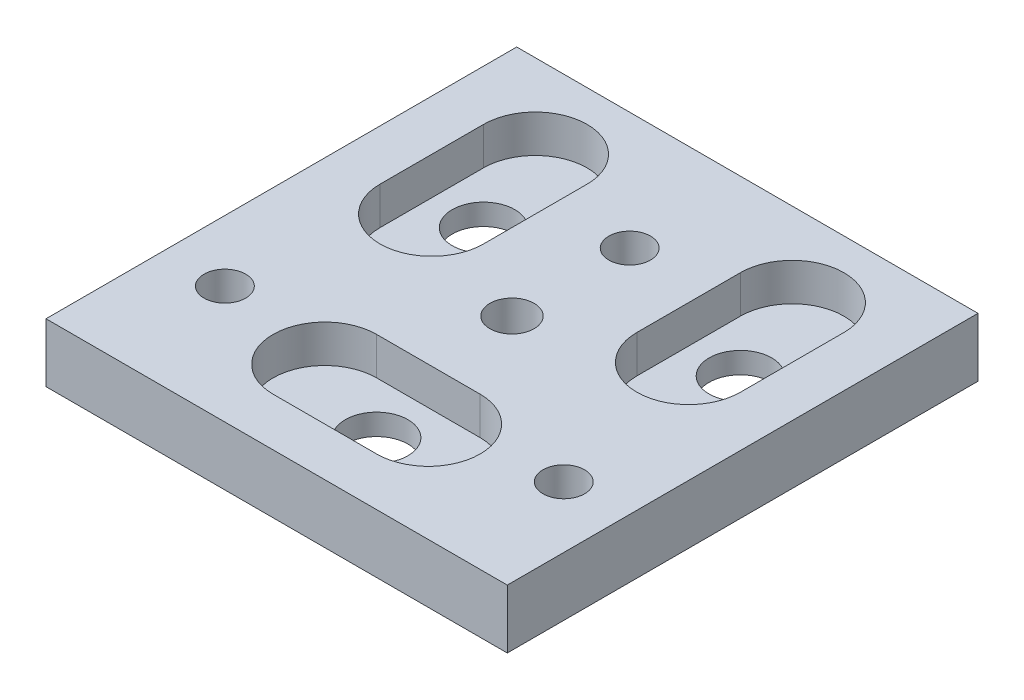
SolidWorks part; units mm, degrees
material "AISI 304"
ref_plane "Front Plane" through (0, 0, 0) normal (0, 0, 1) x (1, 0, 0)
ref_plane "Top Plane" through (0, 0, 0) normal (0, 1, 0) x (1, 0, 0)
ref_plane "Right Plane" through (0, 0, 0) normal (1, 0, 0) x (0, 0, -1)
sketch "Sketch1" plane through (0, 0, 0) normal (0, 1, 0) x (1, 0, 0)
  line L1 (-24.892, 25.4) -> (24.892, 25.4)
  line L2 (-24.892, 25.4) -> (-24.892, -25.4)
  line L3 (-24.892, -25.4) -> (24.892, -25.4)
  line L4 (24.892, 25.4) -> (24.892, -25.4)
  dimension "D1" = 50.8
  dimension "D2" = 49.784
  dimension "D3" = 24.892
  dimension "D4" = 25.4
extrude "Boss-Extrude1" add sketch "Sketch1" along normal blind 6.35
hole_wizard "#8 Clearance Hole1" positions "Sketch5" profile "Sketch4" hole size "#8" standard "ANSI Inch" end condition through all
sketch "Sketch5" plane through (0, 6.35, 0) normal (0, 1, 0) x (1, 0, 0)
  line L1 (24.892, 25.4) -> (-24.892, 25.4) construction
  line L3 (-24.892, -25.4) -> (24.892, -25.4) construction
  point P0 (-18.288, 12.7)
  point P6 (18.288, 12.7)
  point P21 (0, -12.7)
  dimension "D1" = 12.7
  dimension "D2" = 12.7
  dimension "D3" = 18.288
  dimension "D4" = 18.288
sketch "Sketch4" plane through (-18.288, 6.35, -12.7) normal (1, 0, 0) x (0, 0, 1)
  line L0 (0, 0) -> (0, 6.35)
  line L1 (0, 6.35) -> (2.2479, 6.35)
  line L2 (2.2479, 6.35) -> (2.2479, 0)
  line L5 (2.2479, 0) -> (0, 0)
  line L11 (0, -6.35) -> (0, 107.95) construction
  dimension "Thru Hole Dia." = 4.4958
  dimension "Thru Hole Depth" = 6.35
hole_wizard "1/4 Clearance Hole1" positions "Sketch7" profile "Sketch6" hole size "1/4" standard "ANSI Inch" end condition through all
sketch "Sketch7" plane through (0, 6.35, 0) normal (0, 1, 0) x (1, 0, 0)
  point P0 (0, 14.6101)
  point P2 (-13.8608, -10.7899)
  point P4 (13.8608, -10.7899)
  dimension "D1" = 14.6101
  dimension "D2" = 10.7899
  dimension "D3" = 13.8608
  dimension "D4" = 27.7216
sketch "Sketch6" plane through (0, 6.35, -14.6101) normal (1, 0, 0) x (0, 0, 1)
  line L0 (0, 0) -> (0, 6.35)
  line L1 (0, 6.35) -> (3.3782, 6.35)
  line L2 (3.3782, 6.35) -> (3.3782, 0)
  line L5 (3.3782, 0) -> (0, 0)
  line L11 (0, -6.35) -> (0, 107.95) construction
  dimension "Thru Hole Dia." = 6.7564
  dimension "Thru Hole Depth" = 6.35
sketch "Sketch8" plane through (0, 0, 0) normal (0, -1, 0) x (1, 0, 0)
  line L2 (-19.4488, 16.3779) -> (-19.4488, 5.2019)
  line L4 (-8.2728, 16.3779) -> (-8.2728, 5.2019)
  line L6 (8.2728, 16.3779) -> (8.2728, 5.2019)
  line L8 (19.4488, 16.3779) -> (19.4488, 5.2019)
  line L9 (-5.588, -9.0221) -> (5.588, -9.0221)
  line L11 (-5.588, -20.1981) -> (5.588, -20.1981)
  circle A0 centre (-13.8608, 10.7899) radius 3.3782 construction
  circle A1 centre (13.8608, 10.7899) radius 3.3782 construction
  circle A2 centre (0, -14.6101) radius 3.3782 construction
  arc A3 (-19.4488, 16.3779) -> (-8.2728, 16.3779) centre (-13.8608, 16.3779) cw
  arc A4 (-19.4488, 5.2019) -> (-8.2728, 5.2019) centre (-13.8608, 5.2019) ccw
  arc A5 (8.2728, 16.3779) -> (19.4488, 16.3779) centre (13.8608, 16.3779) cw
  arc A6 (19.4488, 5.2019) -> (8.2728, 5.2019) centre (13.8608, 5.2019) cw
  arc A7 (-5.588, -9.0221) -> (-5.588, -20.1981) centre (-5.588, -14.6101) ccw
  arc A8 (5.588, -9.0221) -> (5.588, -20.1981) centre (5.588, -14.6101) cw
  dimension "D1" = 11.176
  dimension "D2" = 5.588
  dimension "D3" = 5.588
  dimension "D5" = 11.176
  dimension "D6" = 5.588
  dimension "D7" = 5.588
  dimension "D8" = 5.588
extrude "Cut-Extrude1" cut sketch "Sketch8" against normal blind 4.064
sketch "Sketch9" plane through (0, 6.35, 0) normal (0, 1, 0) x (1, 0, 0)
  circle A0 centre (0, 0) radius 2.3813
  dimension "D1" = 4.7625
extrude "Cut-Extrude2" cut sketch "Sketch9" against normal through all
move or copy body "Body-Move/Copy1" bodies to move or copy 105 copy no rotation origin (0, 3.175, 0) rotation axis (1, 0, 0) rotation angle 180
